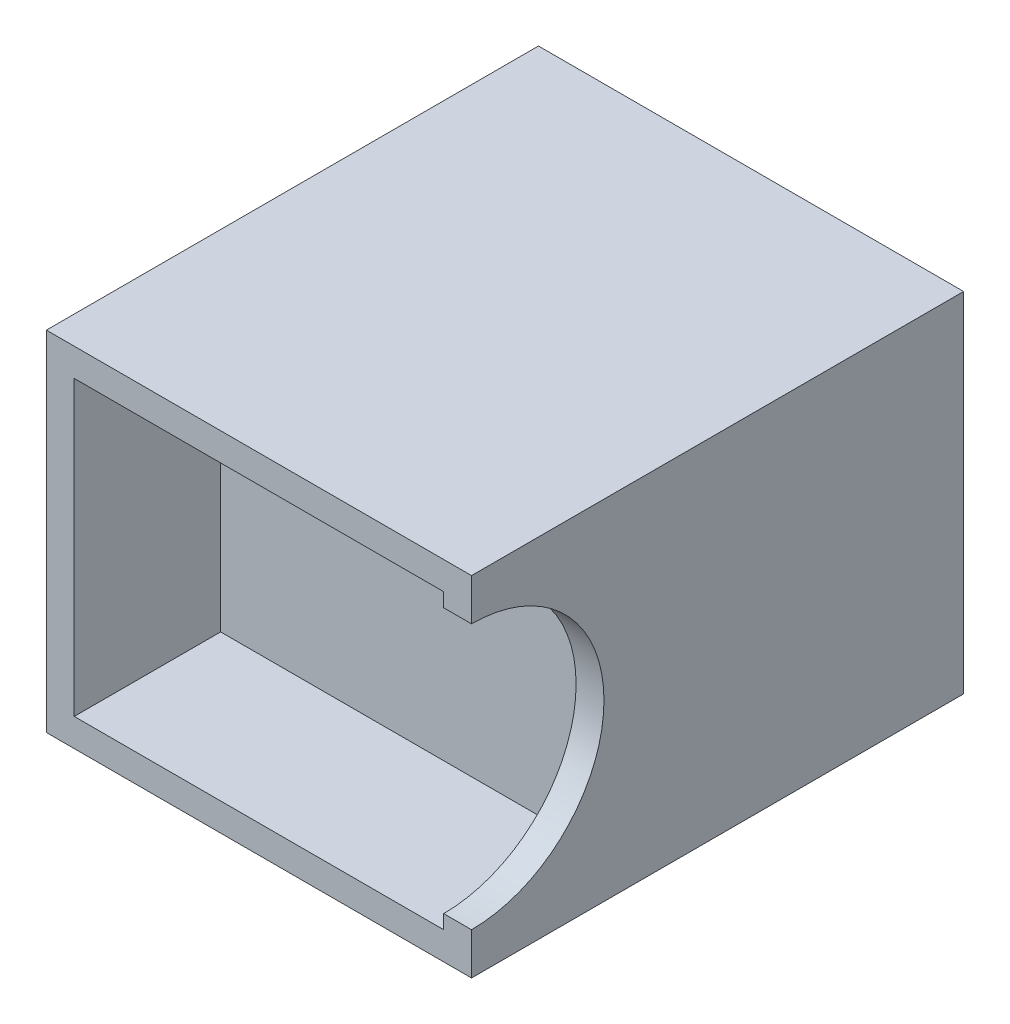
SolidWorks part; units mm, degrees
ref_plane "Front Plane" through (0, 0, 0) normal (0, 0, 1) x (1, 0, 0)
ref_plane "Top Plane" through (0, 0, 0) normal (0, 1, 0) x (1, 0, 0)
ref_plane "Right Plane" through (0, 0, 0) normal (1, 0, 0) x (0, 0, -1)
sketch "Sketch1" plane through (0, 0, 0) normal (0, 0, 1) x (1, 0, 0)
  line L1 (0, 0) -> (61, 0)
  line L2 (0, 0) -> (0, 50)
  line L3 (0, 50) -> (61, 50)
  line L4 (61, 0) -> (61, 50)
  line L5 (4, 46) -> (57, 46)
  line L6 (4, 46) -> (4, 4)
  line L7 (4, 4) -> (57, 4)
  line L8 (57, 46) -> (57, 4)
  dimension "D1" = 50
  dimension "D2" = 61
  dimension "D3" = 4
  dimension "D4" = 4
  dimension "D5" = 4
  dimension "D6" = 4
extrude "Boss-Extrude1" add sketch "Sketch1" along normal blind 70.6
sketch "Sketch2" plane through (0, 0, 0) normal (0, 0, -1) x (-1, 0, 0)
  line L1 (0, 0) -> (-61, 0)
  line L2 (0, 0) -> (0, 50)
  line L3 (0, 50) -> (-61, 50)
  line L4 (-61, 0) -> (-61, 50)
extrude "Boss-Extrude2" add sketch "Sketch2" against normal blind 49.6
sketch "Sketch3" plane through (61, 0, 0) normal (1, 0, 0) x (0, 0, -1)
  line L0 (-70.6, 0) -> (-70.6, 50) construction
  circle A0 centre (-70.6, 25) radius 19
  dimension "D1" = 38
extrude "Cut-Extrude1" cut sketch "Sketch3" against normal blind 10
